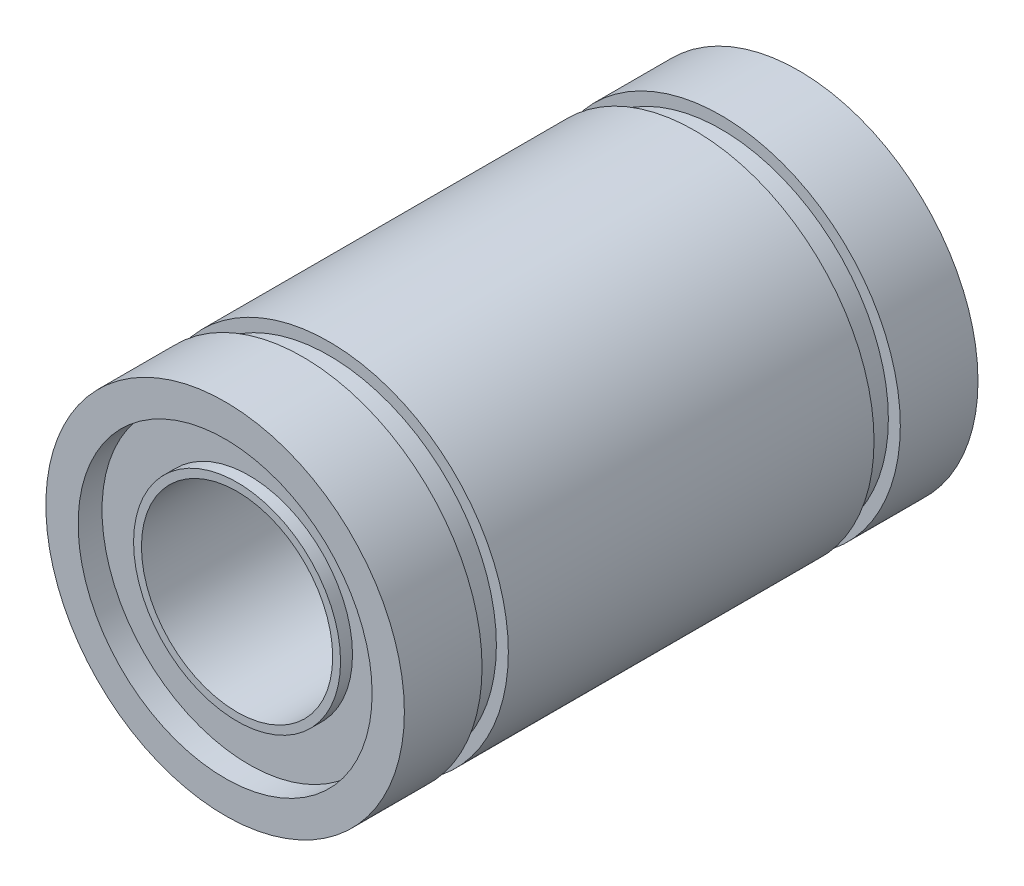
SolidWorks part; units mm, degrees
ref_plane "Front Plane" through (0, 0, 0) normal (0, 0, 1) x (1, 0, 0)
ref_plane "Top Plane" through (0, 0, 0) normal (0, 1, 0) x (1, 0, 0)
ref_plane "Right Plane" through (0, 0, 0) normal (1, 0, 0) x (0, 0, -1)
sketch "Sketch1" plane through (0, 0, 0) normal (0, 1, 0) x (1, 0, 0)
  line L0 (4.33, -0.5) -> (4, -0.5)
  line L1 (4, -0.5) -> (4, -23.5)
  line L2 (4, -23.5) -> (4.33, -23.5)
  line L3 (4.33, -23.5) -> (4.33, -23)
  line L4 (4.33, -23) -> (6.15, -23)
  line L5 (6.15, -23) -> (6.15, -24)
  line L6 (6.15, -24) -> (7.5, -24)
  line L7 (7.5, -24) -> (7.5, -20.75)
  line L8 (7.5, -20.75) -> (7, -20.75)
  line L9 (7, -20.75) -> (7, -19.65)
  line L10 (7, -19.65) -> (7.5, -19.65)
  line L11 (7.5, -19.65) -> (7.5, -4.35)
  line L12 (7.5, -4.35) -> (7, -4.35)
  line L13 (7, -4.35) -> (7, -3.25)
  line L14 (7, -3.25) -> (7.5, -3.25)
  line L15 (7.5, -3.25) -> (7.5, 0)
  line L16 (7.5, 0) -> (6.15, 0)
  line L17 (6.15, 0) -> (6.15, -1)
  line L18 (6.15, -1) -> (4.33, -1)
  line L19 (4.33, -1) -> (4.33, -0.5)
  line L20 (0, 0) -> (0, -24) construction
revolve "Revolve1" add sketch "Sketch1" angle 360 about L20
